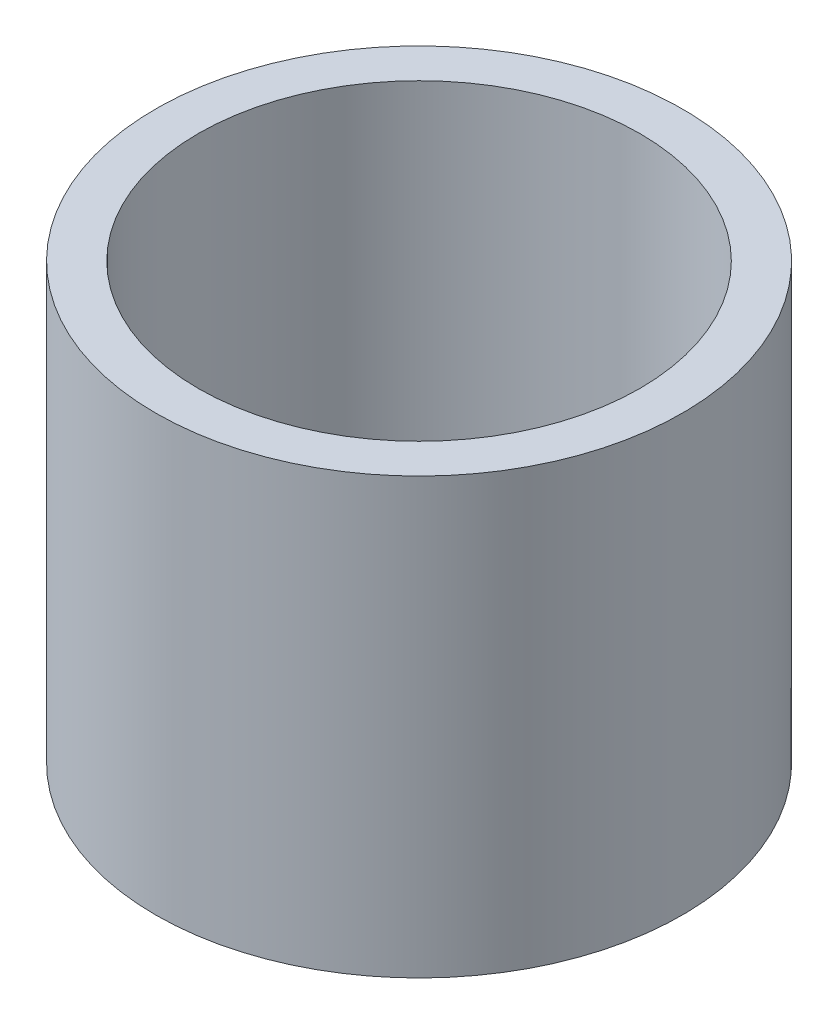
SolidWorks part; units mm, degrees
ref_plane "Front Plane" through (0, 0, 0) normal (0, 0, 1) x (1, 0, 0)
ref_plane "Top Plane" through (0, 0, 0) normal (0, 1, 0) x (1, 0, 0)
ref_plane "Right Plane" through (0, 0, 0) normal (1, 0, 0) x (0, 0, -1)
sketch "Sketch1" plane through (0, 0, 0) normal (0, 1, 0) x (1, 0, 0)
  circle A0 centre (0, 0) radius 30.3
  circle A1 centre (0, 0) radius 25.4
  dimension "D1" = 60.6
  dimension "D2" = 50.8
extrude "Boss-Extrude1" add sketch "Sketch1" along normal blind 50
